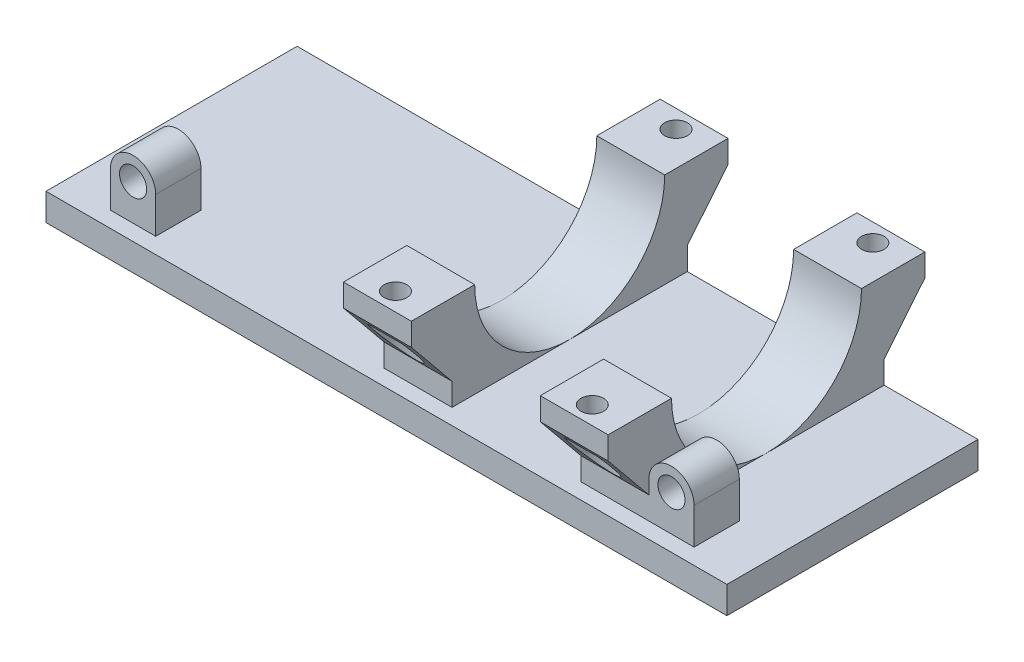
SolidWorks part; units mm, degrees
ref_plane "Alzado" through (0, 0, 0) normal (0, 0, 1) x (1, 0, 0)
ref_plane "Planta" through (0, 0, 0) normal (0, 1, 0) x (1, 0, 0)
ref_plane "Vista lateral" through (0, 0, 0) normal (1, 0, 0) x (0, 0, -1)
sketch "Croquis1" plane through (0, 0, 0) normal (0, 1, 0) x (1, 0, 0)
  line L1 (74.5, -26.5) -> (-74.5, -26.5)
  line L2 (74.5, -26.5) -> (74.5, 26.5)
  line L3 (74.5, 26.5) -> (-74.5, 26.5)
  line L4 (-74.5, -26.5) -> (-74.5, 26.5)
  line L5 (74.5, -26.5) -> (-74.5, 26.5) construction
  line L6 (74.5, 26.5) -> (-74.5, -26.5) construction
  point P0 (0, 0)
  dimension "D1" = 149
  dimension "D2" = 53
extrude "Saliente-Extruir1" add sketch "Croquis1" along normal blind 6
ref_plane "Plano1" through (51.5, 0, 0) normal (1, 0, 0) x (0, 0, -1)
sketch "Croquis2" plane through (51.5, 0, 0) normal (1, 0, 0) x (0, 0, -1)
  line L0 (-26.5, 6) -> (26.5, 6) construction
  line L1 (26, 6) -> (-26, 6)
  line L2 (26, 6) -> (26, 27)
  line L4 (-26, 6) -> (-26, 27)
  arc A0 (26, 27) -> (-26, 27) centre (0, 27) ccw
  point P6 (0, 6)
  dimension "D1" = 52
  dimension "D2" = 21
extrude "Saliente-Extruir2" add sketch "Croquis2" against normal blind 15 contours L2 A0 L4 L1
ref_plane "Plano4" through (8, 0, 0) normal (-1, 0, 0) x (0, 0, 1)
sketch "Croquis5" plane through (8, 0, 0) normal (-1, 0, 0) x (0, 0, 1)
  line L0 (-26, 6) -> (26, 6) construction
  line L1 (26, 6) -> (26, 27) construction
  line L2 (-26, 6) -> (-26, 27) construction
  line L3 (-26, 6) -> (26, 6)
  line L4 (26, 6) -> (26, 27)
  line L5 (-26, 6) -> (-26, 27)
  arc A0 (26, 27) -> (-26, 27) centre (0, 27) ccw construction
  arc A1 (26, 27) -> (-26, 27) centre (0, 27) ccw
extrude "Saliente-Extruir5" add sketch "Croquis5" along normal blind 15
sketch "Croquis3" plane through (51.5, 0, 0) normal (1, 0, 0) x (0, 0, -1)
  circle A0 centre (0, 27) radius 21
  dimension "D1" = 42
extrude "Cortar-Extruir2" cut sketch "Croquis3" against normal through all contours A0
ref_plane "Plano5" through (0, 0, 26) normal (0, 0, 1) x (1, 0, 0)
sketch "Croquis6" plane through (0, 0, 26) normal (0, 0, 1) x (1, 0, 0)
  line L0 (-74.5, 6) -> (74.5, 6) construction
  line L1 (61.5, 6) -> (51.5, 6)
  line L2 (61.5, 6) -> (61.5, 14)
  line L4 (51.5, 6) -> (51.5, 14)
  line L6 (51.5, 6) -> (51.5, 27) construction
  arc A0 (61.5, 14) -> (51.5, 14) centre (56.5, 14) ccw
  circle A1 centre (56.5, 14) radius 3
  dimension "D3" = 6
  dimension "D1" = 10
  dimension "D2" = 8
  dimension "D4" = 0
extrude "Saliente-Extruir11" add sketch "Croquis6" against normal blind 10 separate body
mirror "Simetría10" [suppressed] about plane through (0, 0, 0) normal (1, 0, 0)
sketch "Croquis10" plane through (0, 0, 26.5) normal (0, 0, 1) x (1, 0, 0)
  line L4 (-74.5, 0) -> (74.5, 0)
  line L5 (74.5, 0) -> (74.5, 6)
  line L6 (74.5, 6) -> (-74.5, 6)
  line L7 (-74.5, 6) -> (-74.5, 0)
  line L8 (-74.5, 0) -> (74.5, 0)
  line L9 (74.5, 0) -> (74.5, 6)
  line L10 (74.5, 6) -> (-74.5, 6)
  line L11 (-74.5, 6) -> (-74.5, 0)
  dimension "D1" = 0
extrude "Saliente-Extruir23" add sketch "Croquis10" along normal blind 3
sketch "Croquis11" plane through (0, 6, 0) normal (0, 1, 0) x (1, 0, 0)
  line L0 (74.5, -29.5) -> (-74.5, -29.5) construction
  line L1 (74.5, 26.5) -> (72.25, 26.5)
  line L2 (74.5, 26.5) -> (74.5, -29.5)
  line L3 (74.5, -29.5) -> (72.25, -29.5)
  line L4 (72.25, 26.5) -> (72.25, -29.5)
  dimension "D1" = 2.25
extrude "Cortar-Extruir3" cut sketch "Croquis11" against normal through all
sketch "Croquis12" plane through (-74.5, 0, 0) normal (-1, 0, 0) x (0, 0, 1)
  line L4 (-26.5, 0) -> (29.5, 0)
  line L5 (29.5, 0) -> (29.5, 6)
  line L6 (29.5, 6) -> (-26.5, 6)
  line L7 (-26.5, 6) -> (-26.5, 0)
  line L8 (-26.5, 0) -> (29.5, 0)
  line L9 (29.5, 0) -> (29.5, 6)
  line L10 (29.5, 6) -> (-26.5, 6)
  line L11 (-26.5, 6) -> (-26.5, 0)
  dimension "D1" = 0
extrude "Saliente-Extruir24" add sketch "Croquis12" along normal blind 3.75
ref_plane "Plano6" through (-3, 0, 0) normal (1, 0, 0) x (0, 0, -1)
mirror "Simetría11" about plane through (-3, 0, 0) normal (1, 0, 0) of bodies 108
sketch "Croquis13" plane through (0, 6, 0) normal (0, 1, 0) x (1, 0, 0)
  line L0 (-78.25, -29.5) -> (-78.25, 26.5) construction
  line L1 (72.25, 26.5) -> (-78.25, 26.5)
  line L2 (72.25, 26.5) -> (72.25, 26)
  line L3 (72.25, 26) -> (-78.25, 26)
  line L4 (-78.25, 26.5) -> (-78.25, 26)
  line L5 (-7, 26) -> (8, 26) construction
extrude "Cortar-Extruir4" cut sketch "Croquis13" against normal through all
ref_plane "Plano7" through (0, 27, 0) normal (0, -1, 0) x (-1, 0, 0)
sketch "Croquis14" plane through (0, 27, 0) normal (0, -1, 0) x (-1, 0, 0)
  line L1 (84.7136, -38.0167) -> (-84.7136, -38.0167)
  line L2 (84.7136, -38.0167) -> (84.7136, 38.0167)
  line L3 (84.7136, 38.0167) -> (-84.7136, 38.0167)
  line L4 (-84.7136, -38.0167) -> (-84.7136, 38.0167)
  line L5 (84.7136, -38.0167) -> (-84.7136, 38.0167) construction
  line L6 (84.7136, 38.0167) -> (-84.7136, -38.0167) construction
  point P0 (0, 0)
extrude "Cortar-Extruir5" cut sketch "Croquis14" against normal through all
sketch "Croquis15" plane through (51.5, 0, 0) normal (1, 0, 0) x (0, 0, -1)
  line L0 (-26, 27) -> (-35, 27)
  line L1 (-26, 8.25) -> (-26, -8.25) construction
  line L2 (-35, 27) -> (-35, 22)
  line L3 (-35, 22) -> (-26, 11)
  line L4 (-26, 11) -> (-26, 27)
  line L5 (-26, 27) -> (-21, 27) construction
  dimension "D1" = 9
  dimension "D2" = 5
  dimension "D3" = 16
extrude "Saliente-Extruir25" add sketch "Croquis15" against normal blind 15
sketch "Croquis16" plane through (0, 27, 0) normal (0, 1, 0) x (1, 0, 0)
  line L0 (36.5, -35) -> (51.5, -35) construction
  circle A0 centre (44, -31) radius 2.5
  point P4 (44, -35)
  dimension "D2" = 5
  dimension "D1" = 4
extrude "Cortar-Extruir6" cut sketch "Croquis16" against normal blind 10
ref_plane "Plano8" through (0, 20.17, 0) normal (0, 1, 0) x (1, 0, 0)
sketch "Croquis17" plane through (0, 20.17, 0) normal (0, 1, 0) x (1, 0, 0)
  circle A0 centre (44, -31) radius 4.5
  dimension "D1" = 9
extrude "Cortar-Extruir7" cut sketch "Croquis17" against normal blind 10
ref_plane "Plano9" through (22.25, 0, 0) normal (-1, 0, 0) x (0, 0, 1)
mirror "Simetría14" about plane through (0, 0, 0) normal (0, 0, 1) of "Saliente-Extruir25", "Cortar-Extruir6", "Cortar-Extruir7" second plane through (22.25, 0, 0) second plane normal (-1, 0, 0)
